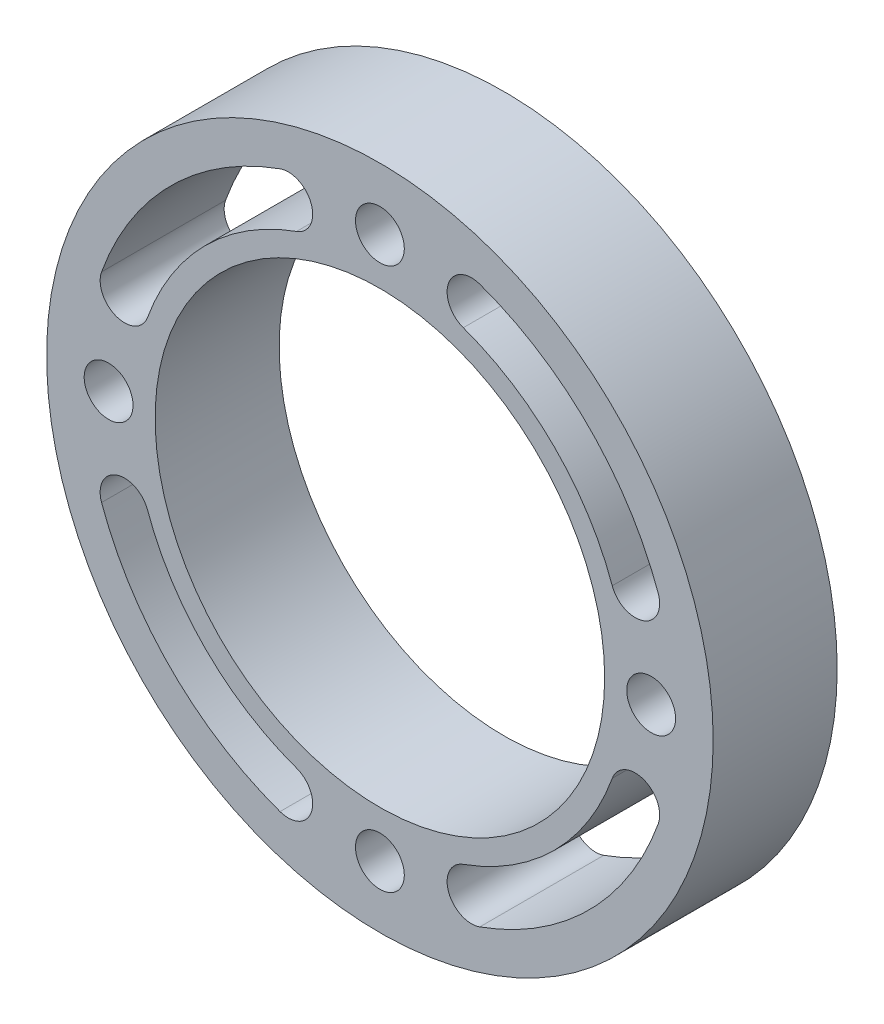
SolidWorks part; units mm, degrees
material "Thornel Mat VMA"
ref_plane "前视基准面" through (0, 0, 0) normal (0, 0, 1) x (1, 0, 0)
ref_plane "上视基准面" through (0, 0, 0) normal (0, 1, 0) x (1, 0, 0)
ref_plane "右视基准面" through (0, 0, 0) normal (1, 0, 0) x (0, 0, -1)
sketch "草图1" plane through (0, 0, 0) normal (0, 0, 1) x (1, 0, 0)
  line L0 (0, 0) -> (-50000, 0) construction
  line L1 (0, 0) -> (0, 50000) construction
  circle A0 centre (0, 0) radius 14.5
  circle A1 centre (0, 0) radius 17.5 construction
  circle A2 centre (0, 0) radius 21.5
  circle A3 centre (0, 17.5) radius 1.575
  circle A4 centre (17.5, 0) radius 1.575
  circle A5 centre (0, -17.5) radius 1.575
  circle A6 centre (-17.5, 0) radius 1.575
  arc A9 (-5.3792, 14.989) -> (-6.4432, 17.9539) centre (-5.9112, 16.4714) ccw
  arc A10 (-17.9539, 6.4432) -> (-14.989, 5.3792) centre (-16.4714, 5.9112) ccw
  arc A11 (-6.4432, 17.9539) -> (-17.9539, 6.4432) centre (0, 0) ccw
  arc A12 (-5.3792, 14.989) -> (-14.989, 5.3792) centre (0, 0) ccw
  arc A13 (5.3792, 14.989) -> (14.989, 5.3792) centre (0, 0) cw
  arc A14 (6.4432, 17.9539) -> (17.9539, 6.4432) centre (0, 0) cw
  arc A15 (17.9539, 6.4432) -> (14.989, 5.3792) centre (16.4714, 5.9112) cw
  arc A16 (5.3792, 14.989) -> (6.4432, 17.9539) centre (5.9112, 16.4714) cw
  arc A17 (5.3792, -14.989) -> (6.4432, -17.9539) centre (5.9112, -16.4714) ccw
  arc A18 (17.9539, -6.4432) -> (14.989, -5.3792) centre (16.4714, -5.9112) ccw
  arc A19 (6.4432, -17.9539) -> (17.9539, -6.4432) centre (0, 0) ccw
  arc A20 (5.3792, -14.989) -> (14.989, -5.3792) centre (0, 0) ccw
  arc A21 (-5.3792, -14.989) -> (-14.989, -5.3792) centre (0, 0) cw
  arc A22 (-6.4432, -17.9539) -> (-17.9539, -6.4432) centre (0, 0) cw
  arc A23 (-17.9539, -6.4432) -> (-14.989, -5.3792) centre (-16.4714, -5.9112) cw
  arc A24 (-5.3792, -14.989) -> (-6.4432, -17.9539) centre (-5.9112, -16.4714) cw
  point P16 (0, 0)
  dimension "D1" = 29
  dimension "D2" = 35
  dimension "D3" = 4
  dimension "D4" = 3.15
  dimension "D8" = 1.575
  dimension "D9" = 19.075
  dimension "D10" = 15.925
  dimension "D11" = 1.575
  dimension "D6" = 6
  dimension "D7" = 6
  dimension "D5" = 4
extrude "凸台-拉伸1" add sketch "草图1" along normal blind 8
